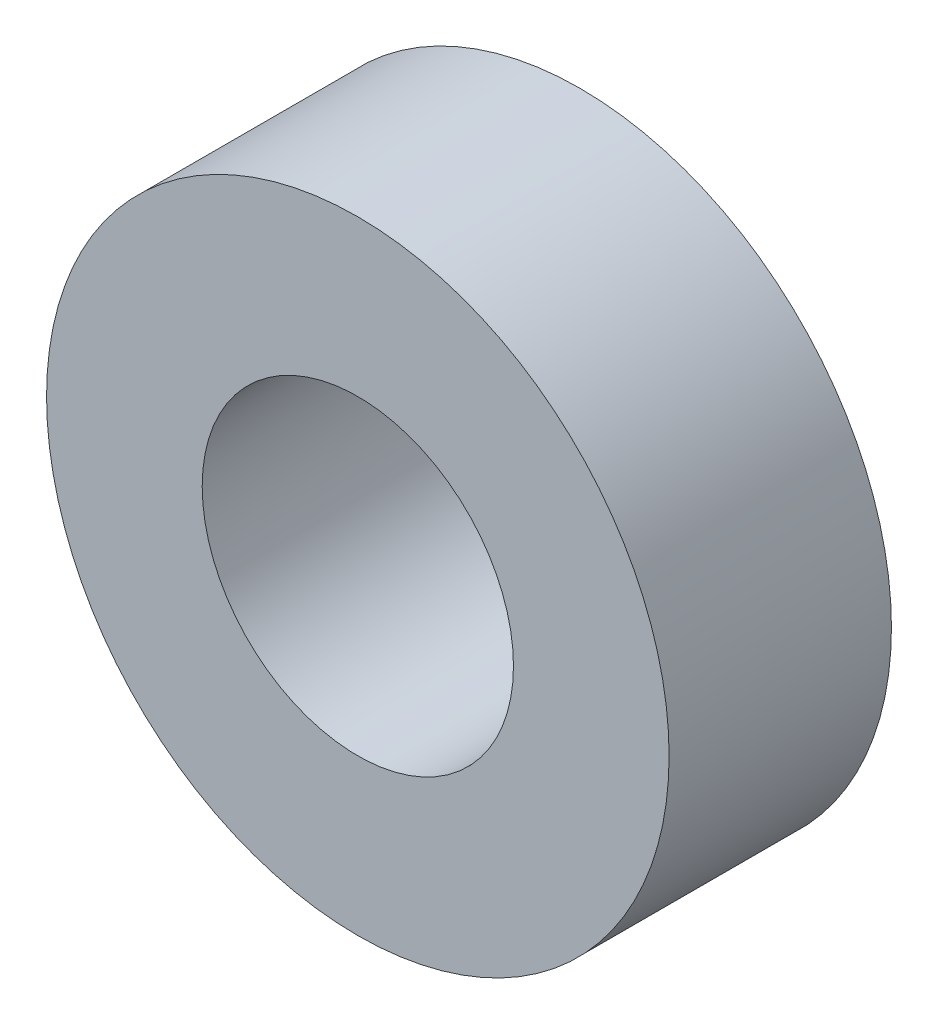
SolidWorks part; units mm, degrees
ref_plane "Front Plane" through (0, 0, 0) normal (0, 0, 1) x (1, 0, 0)
ref_plane "Top Plane" through (0, 0, 0) normal (0, 1, 0) x (1, 0, 0)
ref_plane "Right Plane" through (0, 0, 0) normal (1, 0, 0) x (0, 0, -1)
sketch "Sketch1" plane through (0, 0, 0) normal (0, 0, 1) x (1, 0, 0)
  circle A0 centre (0, 0) radius 7
  circle A1 centre (0, 0) radius 3.5
  dimension "D1" = 7
  dimension "D2" = 14
extrude "Boss-Extrude1" add sketch "Sketch1" along normal blind 5
equation "\"Ns\"= 24"
equation "\"Nr\"= 78"
equation "\"num_planet\"= 3"
equation "\"module\"= 0.6"
equation "\"pressure angle\"= 20.0"
equation "\"h_a\"= 0.6"
equation "\"h_b\"= 0.75"
equation "\"clr_tip_root\"= 0.15000000000000002"
equation "\"dp_s\"= 14.399999999999999"
equation "\"db_s\"= 13.53157373931708"
equation "\"fw_s_calc\"= 16.210783717444997"
equation "\"alpha_s\"= 0.8539582918412343"
equation "\"beta_s\"= 5.792083416317531"
equation "\"pressure_angle\"= 20.0"
equation "\"h_f\"= 0.75"
equation "\"dp_r\"= 46.8"
equation "\"db_r\"= 43.97761465278051"
equation "\"fw_r\"= 22.845791438896047"
equation "\"alpha_r\"= 0.8539582918412556"
equation "\"beta_r\"= 4.015608891374819"
equation "\"bearing_ID\"= 45"
equation "\"bearing_OD\"= 58"
equation "\"bearing_height\"= 7"
equation "\"clearance_planet\"= 1.5"
equation "\"case_dist\"= 24.210783717444997"
equation "\"Motor_case_OD_max\"= 88.5"
equation "\"case_mounting_PCD\"= 81.0"
equation "\"bearing mount thickness\"= IIF((\"bearing_OD\" + \"output_mounting_hole_dia\" * 4) > (\"Nr\" * \"module\" + 2 * \"h_b\"), \"output_mounting_hole_dia\" * 2, ((\"Nr\" * \"module\" + 2 * \"h_b\" - (\"bearing_OD\" + \"output_mounting_hole_dia\" * 4)) / 2) + \"output_mounting_hole_dia\" * 2 + \"standard_clearance_1_5mm\")"
equation "\"case_mounting_hole_dia\"= 3"
equation "\"output_mounting_PCD\"= 66"
equation "\"output_mounting_hole_dia\"= 4"
equation "\"clearance_case_mount_holes_shell_thickness\"= 1"
equation "\"motor_case_OD_base\"= 79.0"
equation "\"sec_carrier_thickness\"= 5"
equation "\"sun_coupler_hub_thickness\"= 4"
equation "\"clearance_sun_coupler_sec_carrier\"= 1.5"
equation "\"clearance_motor_and_case\"= 5"
equation "\"motor_OD\"= 64"
equation "\"Motor_case_thickness\"= 2.5"
equation "\"Motor_case_ID\"= 74"
equation "\"case_mounting_hole_shift\"= 1.0"
equation "\"output_mounting_nut_wrench_size\"= 7"
equation "\"output_mounting_nut_thickness\"= 3.2"
equation "\"case_mounting_hole_allen_socket_dia\"= 5.5"
equation "\"output_mounting_nut_depth\"= 3"
equation "\"case_mounting_bolt_depth\"= 4.5"
equation "\"ring_radial_thickness\"= 7.100000000000001"
equation "\"ring_OD\"= 61.0"
equation "\"ring_to_chamfer_clearance\"= 0.5"
equation "\"Motor_case_OD_base_to_chamfer\"= 5"
equation "\"pattern_offset_from_motor_case_OD_base\"= 3"
equation "\"pattern_bulge_dia\"= 3"
equation "\"pattern_num_bulge\"= 18"
equation "\"pattern_depth\"= 2"
equation "\"motor_height\"= 75"
equation "\"case_mounting_wrench_size\"= 5.5"
equation "\"case_mounting_nut_clearance\"= 2"
equation "\"base_plate_thickness\"= 4"
equation "\"case_mounting_nut_thickness\"= 2.4"
equation "\"case_mounting_surface_height\"= 4"
equation "\"motor_mount_hole_PCD\"= 44"
equation "\"motor_mount_hole_dia\"= 4"
equation "\"motor_mount_hole_num\"= 4"
equation "\"central_hole_offset_from_motor_mount_PCD\"= 5"
equation "\"wire_slot_dist_from_center\"= 22"
equation "\"wire_slot_length\"= 8"
equation "\"wire_slot_radius\"= 2"
equation "\"driver_upper_holes_dist_from_center\"= 29"
equation "\"driver_lower_holes_dist_from_center\"= 13"
equation "\"driver_side_holes_dist_from_center\"= 22.5"
equation "\"driver_mount_holes_dia\"= 3"
equation "\"driver_mount_inserts_OD\"= 4.8"
equation "\"driver_mount_thickness\"= 1.5"
equation "\"driver_mount_height\"= 6"
equation "\"air_flow_hole_offset\"= 3"
equation "\"planet_pin_bolt_dia\"= 2.5"
equation "\"planet_pin_socket_head_dia\"= 4.5"
equation "\"carrier_PCD\"= 34.199999999999996"
equation "\"planet_shaft_dia\"= 5"
equation "\"planet_shaft_step_offset\"= 0.8"
equation "\"carrier_trapezoidal_support_sun_offset\"= 5"
equation "\"carrier_trapezoidal_support_hole_PCD_offset_bearing_ID\"= 4"
equation "\"carrier_trapezoidal_support_hole_dia\"= 3"
equation "\"carrier_trapezoidal_support_hole_socket_head_dia\"= 5.5"
equation "\"carrier_bearing_step_width\"= 1.5"
equation "\"standard_clearance_1_5mm\"= 1.5"
equation "\"standard_fillet_1_5mm\"= 1.5"
equation "\"sun_shaft_bearing_OD\"= 14"
equation "\"sun_shaft_bearing_width\"= 5"
equation "\"standard_bearing_insertion_chamfer\"= 0.5"
equation "\"carrier_trapezoidal_support_hole_wrench_size\"= 5.5"
equation "\"planet_pin_bolt_wrench_size\"= 5"
equation "\"planet_bearing_OD\"= 8"
equation "\"planet_bearing_width\"= 2.5"
equation "\"planet_bore\"= 6"
equation "\"motor_output_hole_PCD\"= 32"
equation "\"motor_output_hole_dia\"= 4"
equation "\"motor_output_hole_num\"= 4"
equation "\"sun_shaft_bearing_ID\"= 7"
equation "\"sun_hub_dia\"= 42.0"
equation "\"sun_central_bolt_dia\"= 3"
equation "\"sun_central_bolt_socket_head_dia\"= 5.5"
equation "\"fw_s_used\"= 48.55657515634104"
equation "\"motor_output_hole_CSK_OD\"= 8"
equation "\"motor_output_hole_CSK_head_height\"= 2.0"
equation "\"D1@Sketch1\"=\"sun_shaft_bearing_ID\""
equation "\"D2@Sketch1\"=\"sun_shaft_bearing_OD\""
equation "\"D1@Boss-Extrude1\"=\"sun_shaft_bearing_width\""
equation "\"Np_b\"= 33"
equation "\"dp_p_b\"= 19.8"
equation "\"db_p_b\"= 18.605913891560988"
equation "\"fw_p_s\"= 24.345791438896047"
equation "\"alpha_p_b\"= 0.8539582918412414"
equation "\"beta_p_b\"= 3.7466288708629714"
equation "\"bearing_retainer_thickness\"= 2"
equation "\"Np_s\"= 21"
equation "\"fw_p_b\"= 16.210783717444997"
equation "\"dp_p_s\"= 12.6"
equation "\"db_p_s\"= 11.840127021902445"
equation "\"alpha_p_s\"= 0.8539582918412556"
equation "\"beta_p_s\"= 6.86351198774606"
